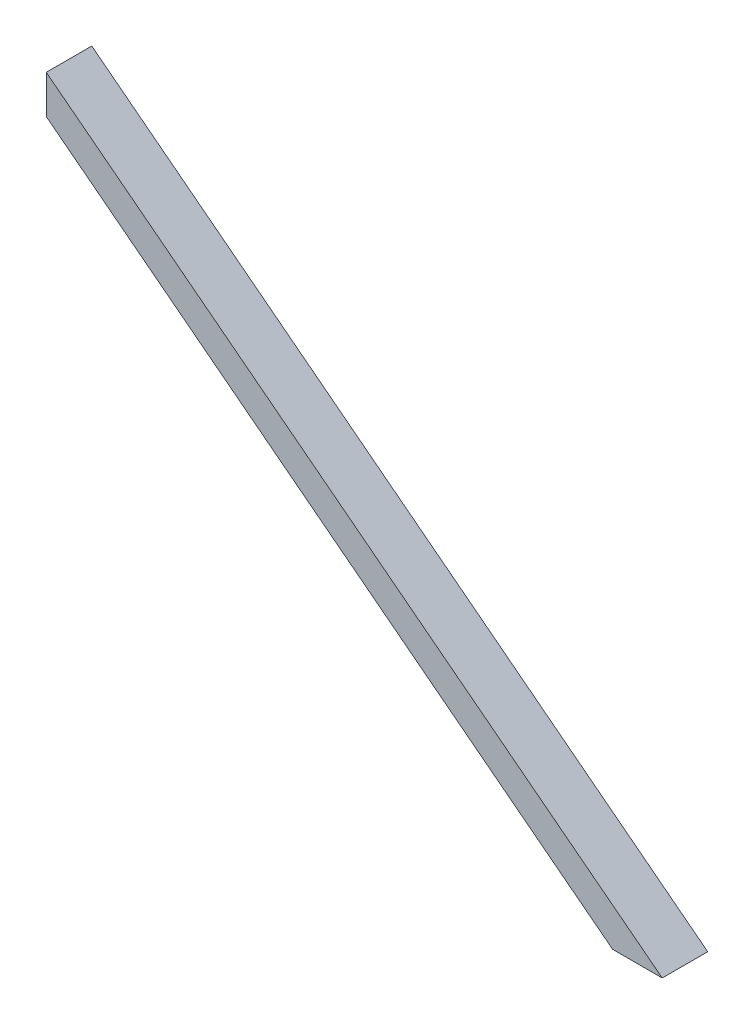
SolidWorks part; units mm, degrees
ref_plane "Front Plane" through (0, 0, 0) normal (0, 0, 1) x (1, 0, 0)
ref_plane "Top Plane" through (0, 0, 0) normal (0, 1, 0) x (1, 0, 0)
ref_plane "Right Plane" through (0, 0, 0) normal (1, 0, 0) x (0, 0, -1)
sketch "Sketch1" plane through (0, 0, 0) normal (0, 0, 1) x (1, 0, 0)
  line L0 (0, 0) -> (0, 398.78) construction
  line L1 (0, 0) -> (515.62, 0) construction
  line L2 (0, 398.78) -> (515.62, 0)
  line L4 (515.62, 0) -> (531.1592, 20.0921)
  line L5 (0, 398.78) -> (15.5392, 418.8721)
  line L6 (15.5392, 418.8721) -> (531.1592, 20.0921)
  point P4 (0, 0)
  dimension "D1" = 398.78
  dimension "D2" = 515.62
  dimension "D3" = 25.4
extrude "Boss-Extrude1" add sketch "Sketch1" against normal blind 38.1
sketch "Sketch3" plane through (0, 0, 0) normal (0, 0, 1) x (1, 0, 0)
  line L0 (15.5392, 418.8721) -> (15.5392, 386.762)
  line L1 (0, 398.78) -> (515.62, 0) construction
  line L3 (15.5392, 386.762) -> (0, 398.78)
  line L4 (0, 398.78) -> (15.5392, 418.8721)
extrude "Cut-Extrude1" cut sketch "Sketch3" against normal blind 127
sketch "Sketch4" plane through (0, 0, 0) normal (0, 0, 1) x (1, 0, 0)
  line L0 (531.1592, 20.0921) -> (489.641, 20.0921)
  line L1 (0, 398.78) -> (515.62, 0) construction
  line L2 (489.641, 20.0921) -> (515.62, 0)
  line L3 (515.62, 0) -> (531.1592, 20.0921)
extrude "Cut-Extrude3" cut sketch "Sketch4" against normal blind 127
